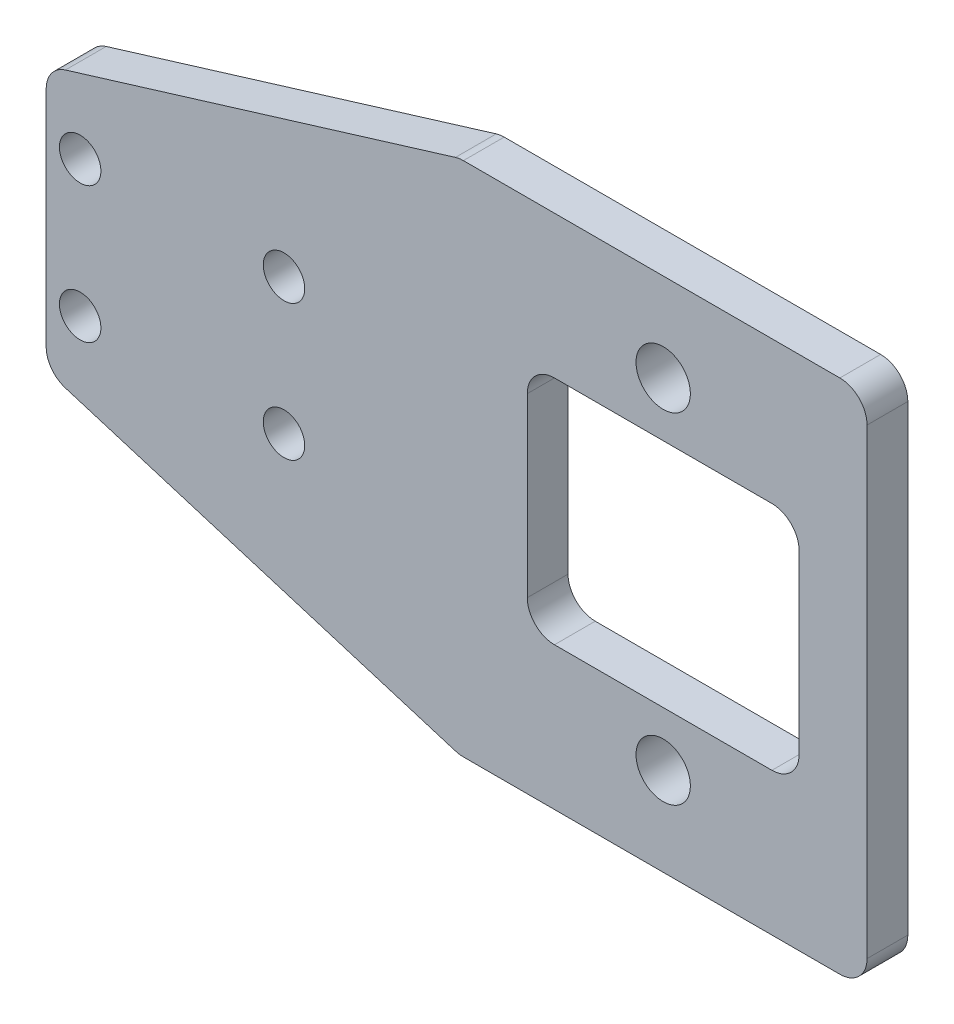
SolidWorks part; units mm, degrees
material "Thornel Mat VMA"
ref_plane "前视基准面" through (0, 0, 0) normal (0, 0, 1) x (1, 0, 0)
ref_plane "上视基准面" through (0, 0, 0) normal (0, 1, 0) x (1, 0, 0)
ref_plane "右视基准面" through (0, 0, 0) normal (1, 0, 0) x (0, 0, -1)
sketch "草图1" plane through (0, 0, 0) normal (0, 0, 1) x (1, 0, 0)
  line L0 (-15, 19) -> (-45.4, 9.7)
  line L1 (-15, -19) -> (15, -19)
  line L2 (-15, -19) -> (-15, 19)
  line L3 (-15, 19) -> (15, 19)
  line L4 (15, -19) -> (15, 19)
  line L5 (0, 19) -> (0, -19) construction
  line L6 (-15, 0) -> (15, 0) construction
  line L7 (-45.4, 9.7) -> (-45.4, -9.7)
  line L8 (-45.4, -9.7) -> (-15, -19)
  line L9 (-45.4, 0) -> (-15, 0) construction
  point P0 (0, 0)
  dimension "D1" = 30
  dimension "D2" = 38
  dimension "D3" = 30.4
  dimension "D4" = 19.4
extrude "凸台-拉伸1" add sketch "草图1" along normal blind 3 contours L7 L8 L2 L0 | L1 L4 L3 L2
sketch "草图2" plane through (0, 0, 3) normal (0, 0, 1) x (1, 0, 0)
  line L0 (15, 19) -> (-15, -19) construction
  line L1 (0, -12.5) -> (0, 12.5) construction
  circle A0 centre (0, 12.5) radius 2
  circle A1 centre (0, -12.5) radius 2
  point P7 (0, 0)
  dimension "D2" = 4
  dimension "D1" = 25
extrude "切除-拉伸1" cut sketch "草图2" against normal blind 3
sketch "草图3" plane through (0, 0, 3) normal (0, 0, 1) x (1, 0, 0)
  line L0 (-27.9, 0) -> (0, 0) construction
  line L1 (-42.9, -5) -> (-27.9, -5) construction
  line L2 (-42.9, -5) -> (-42.9, 5) construction
  line L3 (-42.9, 5) -> (-27.9, 5) construction
  line L4 (-27.9, -5) -> (-27.9, 5) construction
  line L5 (-35.4, 5) -> (-35.4, -5) construction
  line L6 (-42.9, 0) -> (-27.9, 0) construction
  line L7 (-45.4, 9.7) -> (-45.4, -9.7) construction
  circle A0 centre (-42.9, 5) radius 1.525
  circle A1 centre (-27.9, 5) radius 1.525
  circle A2 centre (-42.9, -5) radius 1.525
  circle A3 centre (-27.9, -5) radius 1.525
  point P0 (-35.4, 0)
  dimension "D4" = 3.05
  dimension "D1" = 15
  dimension "D2" = 10
  dimension "D3" = 2.5
extrude "切除-拉伸2" cut sketch "草图3" against normal blind 3
fillet "圆角1" radius 2 6 edges at (-45.4, 9.7, 1.5) (-15, 19, 1.5) (-45.4, -9.7, 1.5) (-15, -19, 1.5) (15, -19, 1.5) (15, 19, 1.5)
sketch "草图4" plane through (0, 0, 3) normal (0, 0, 1) x (1, 0, 0)
  line L0 (15, -17) -> (15, 17) construction
  line L5 (-10, -8.5) -> (10, -8.5)
  line L6 (-10, -8.5) -> (-10, 8.5)
  line L7 (-10, 8.5) -> (10, 8.5)
  line L8 (10, -8.5) -> (10, 8.5)
  line L9 (0, 8.5) -> (0, -8.5) construction
  line L10 (-10, 0) -> (10, 0) construction
  circle A0 centre (0, 12.5) radius 2 construction
  point P0 (0, 0)
  dimension "D1" = 5
  dimension "D2" = 4
extrude "切除-拉伸3" cut sketch "草图4" against normal blind 3
fillet "圆角2" radius 2 4 edges at (-10, 8.5, 1.5) (10, 8.5, 1.5) (-10, -8.5, 1.5) (10, -8.5, 1.5)
